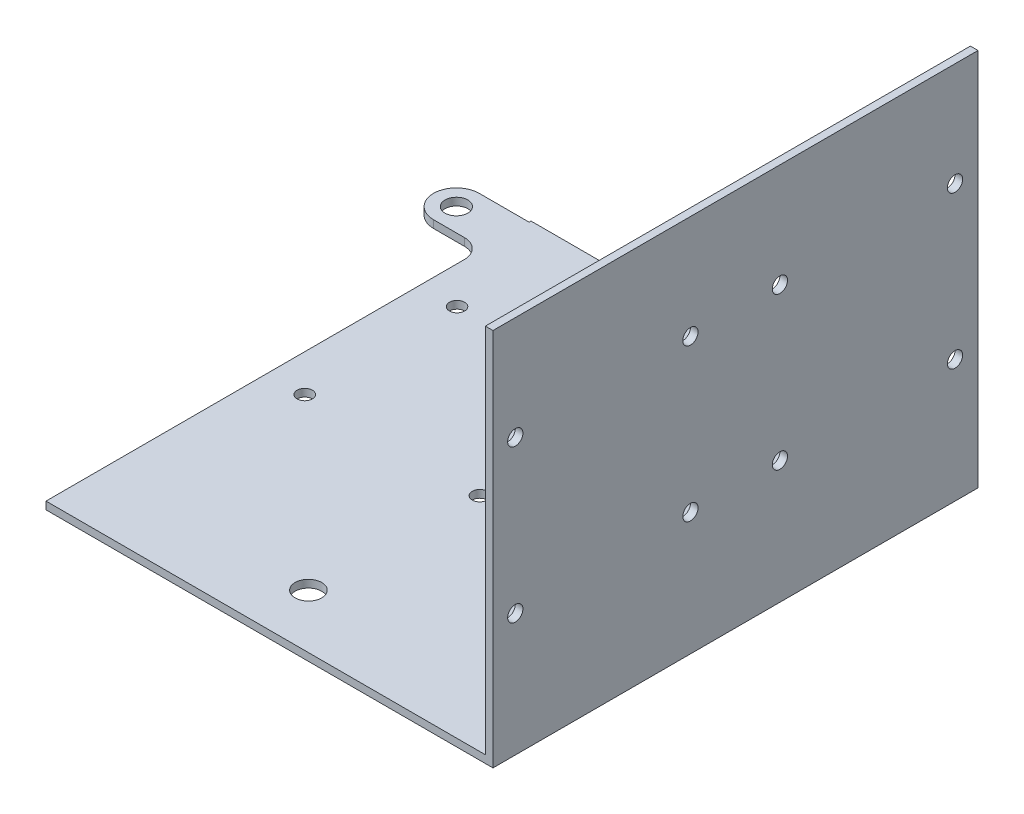
SolidWorks part; units mm, degrees
ref_plane "Спереди" through (0, 0, 0) normal (0, 0, 1) x (1, 0, 0)
ref_plane "Сверху" through (0, 0, 0) normal (0, 1, 0) x (1, 0, 0)
ref_plane "Справа" through (0, 0, 0) normal (1, 0, 0) x (0, 0, -1)
sketch "Эскиз1" plane through (0, 0, 0) normal (1, 0, 0) x (0, 0, -1)
  line L0 (63.696, 69.8758) -> (-63.696, 69.8758)
  line L1 (-0.0869, 69.8758) -> (-0.0869, -69.8758) construction
  line L2 (63.696, -29.624) -> (-63.696, -29.624)
  line L3 (63.696, 69.8758) -> (63.696, -29.624)
  line L4 (-63.696, 69.8758) -> (-63.696, -29.624)
  circle A0 centre (11.6631, 42.626) radius 2
  circle A1 centre (57.6631, 42.626) radius 2
  circle A2 centre (57.6631, 2.626) radius 2
  circle A3 centre (11.6631, 2.626) radius 2
  circle A4 centre (-11.8369, 2.626) radius 2
  circle A5 centre (-57.8369, 2.626) radius 2
  circle A6 centre (-57.8369, 42.626) radius 2
  circle A7 centre (-11.8369, 42.626) radius 2
extrude "Бобышка-Вытянуть1" add sketch "Эскиз1" along normal blind 2
sketch "Эскиз2" plane through (2, 0, 0) normal (1, 0, 0) x (0, 0, -1)
  line L0 (63.696, -29.624) -> (63.696, 69.8758) construction
  line L1 (-63.696, -29.624) -> (63.696, -29.624)
  line L2 (-63.696, -29.624) -> (-63.696, -27.624)
  line L3 (-63.696, -27.624) -> (63.696, -27.624)
  line L4 (63.696, -29.624) -> (63.696, -27.624)
  dimension "D1" = 2
extrude "Бобышка-Вытянуть2" add sketch "Эскиз2" along normal blind 115.4
sketch "Эскиз4" plane through (0, 21.676, 0) normal (0, 1, 0) x (1, 0, 0)
  circle A0 centre (61.65, 34.5126) radius 2
  circle A1 centre (61.65, -5.4874) radius 2
  circle A2 centre (107.65, -5.4874) radius 2
  circle A3 centre (107.65, 34.5126) radius 2
extrude "Вырез-Вытянуть1" cut sketch "Эскиз4" against normal through all
sketch "Эскиз6" plane through (0, -27.624, 0) normal (0, 1, 0) x (1, 0, 0)
  line L0 (77.8375, -49.504) -> (47.5024, -49.504) construction
  line L1 (40.9798, -10.8906) -> (41.0012, 10.7183) construction
  circle A0 centre (62.67, -49.504) radius 3.5
  circle A1 centre (40.9905, -0.0862) radius 3.5
extrude "Вырез-Вытянуть2" cut sketch "Эскиз6" against normal through all
sketch "Эскиз7" plane through (0, -27.624, 0) normal (0, 1, 0) x (1, 0, 0)
  line L0 (130.5, 51.196) -> (117.4, 51.196)
  line L1 (117.4, 63.696) -> (117.4, -63.696) construction
  line L2 (130.5, 63.196) -> (117.4, 63.196)
  line L3 (117.4, 63.196) -> (117.4, 51.196)
  circle A0 centre (130.5, 57.196) radius 3
  arc A1 (130.5, 51.196) -> (130.5, 63.196) centre (130.5, 57.196) ccw
  circle A2 centre (130.5, 57.196) radius 6 construction
  dimension "D1" = 3
extrude "Бобышка-Вытянуть3" add sketch "Эскиз7" against normal blind 2
fillet "Скругление1" radius 5 1 edges at (117.4, -28.624, -51.196)
ref_plane "Плоскость4" through (-15, 0, 0) normal (-1, 0, 0) x (0, 0, 1)
mirror "Зеркальное отражение1" about plane through (-15, 0, 0) normal (-1, 0, 0) of bodies 105
sketch "Эскиз8" plane through (-15, 0, 0) normal (-1, 0, 0) x (0, 0, 1)
  line L1 (-79.5248, 87.1034) -> (82.3523, 87.1034)
  line L2 (-79.5248, 87.1034) -> (-79.5248, -45.968)
  line L3 (-79.5248, -45.968) -> (82.3523, -45.968)
  line L4 (82.3523, 87.1034) -> (82.3523, -45.968)
extrude "Вырез-Вытянуть3" cut sketch "Эскиз8" against normal through all
